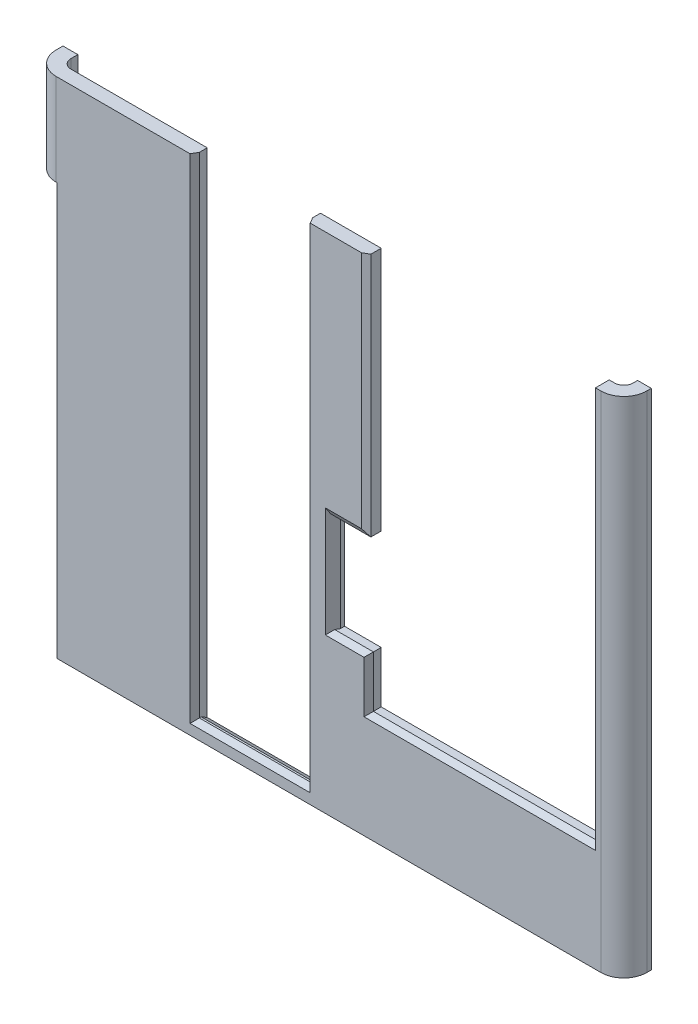
SolidWorks part; units mm, degrees
ref_plane "Front Plane" through (0, 0, 0) normal (0, 0, 1) x (1, 0, 0)
ref_plane "Top Plane" through (0, 0, 0) normal (0, 1, 0) x (1, 0, 0)
ref_plane "Right Plane" through (0, 0, 0) normal (1, 0, 0) x (0, 0, -1)
sketch "Sketch1" plane through (0, 0, 0) normal (0, 0, 1) x (1, 0, 0)
  line L0 (0, -3.575) -> (0, 3.575) construction
  line L1 (-60.5, 55) -> (60.5, 55)
  line L2 (-60.5, 55) -> (-60.5, -55)
  line L3 (-60.5, -55) -> (60.5, -55)
  line L4 (60.5, 55) -> (60.5, -55)
  line L5 (3.575, 0) -> (-3.575, 0) construction
  dimension "D1" = 60.5
  dimension "D2" = 60.5
  dimension "D3" = 55
  dimension "D4" = 55
extrude "Boss-Extrude1" add sketch "Sketch1" along normal blind 3
sketch "Sketch8" plane through (0, 0, 0) normal (0, 0, -1) x (-1, 0, 0)
  line L0 (60.5, -55) -> (-60.5, -55) construction
  line L1 (-60.5, 55) -> (-57.5, 55)
  line L2 (-60.5, 55) -> (-60.5, -55)
  line L3 (-60.5, -55) -> (-57.5, -55)
  line L4 (-57.5, 55) -> (-57.5, -55)
  dimension "D1" = 3
extrude "Boss-Extrude5" add sketch "Sketch8" along normal blind 3
fillet "Fillet4" radius 2 1 edges at (57.5, 0, 0)
fillet "Fillet5" radius 5 1 edges at (60.5, 0, 3)
sketch "Sketch9" plane through (0, 0, -3) normal (0, 0, -1) x (-1, 0, 0)
  line L0 (-57.5, 55) -> (-60.5, 55) construction
  line L1 (-59.5, 55) -> (-58.5, 55)
  line L2 (-59.5, 55) -> (-59.5, -55)
  line L3 (-59.5, -55) -> (-58.5, -55)
  line L4 (-58.5, 55) -> (-58.5, -55)
  line L5 (-60.5, -55) -> (-57.5, -55) construction
  line L6 (-60.5, 55) -> (-60.5, -55) construction
  line L7 (-57.5, -55) -> (-57.5, 55) construction
  dimension "D1" = 1
  dimension "D2" = 1
extrude "Boss-Extrude6" add sketch "Sketch9" along normal blind 2.5
sketch "Sketch10" plane through (0, 55, 0) normal (0, 1, 0) x (1, 0, 0)
  line L0 (58.5, 5.5) -> (58, 3)
  line L1 (57.5, 3) -> (58.5, 3) construction
  line L2 (58, 3) -> (58.5, 3)
  line L3 (58.5, 3) -> (58.5, 5.5)
extrude "Boss-Extrude7" add sketch "Sketch10" against normal through all
sketch "Sketch11" plane through (0, 0, 3) normal (0, 0, 1) x (1, 0, 0)
  line L0 (55.5, 55) -> (-60.5, 55) construction
  line L1 (-33.5, 55) -> (-8.75, 55)
  line L2 (-33.5, 55) -> (-33.5, -52)
  line L3 (-33.5, -52) -> (-8.75, -52)
  line L4 (-8.75, 55) -> (-8.75, -52)
  line L6 (-60.5, 55) -> (-60.5, -55) construction
  line L7 (57.5, -55) -> (57.5, 55) construction
  line L8 (4.5, 55) -> (54.3, 55)
  line L9 (4.5, 55) -> (4.5, -31.75)
  line L10 (4.5, -31.75) -> (54.3, -31.75)
  line L11 (54.3, 55) -> (54.3, -31.75)
  line L12 (-60.5, -55) -> (55.5, -55) construction
  dimension "D1" = 27
  dimension "D2" = 24.75
  dimension "D3" = 3.2
  dimension "D4" = 13.25
  dimension "D5" = 3
  dimension "D6" = 23.25
extrude "Cut-Extrude1" cut sketch "Sketch11" against normal up to surface (3 mm away) up to face at (-2.5, 0, 0)
chamfer "Chamfer1" distance 0.75 angle 60 3 edges at (-33.5, 1.5, 3) (-8.75, 1.5, 3) (-21.125, -52, 3)
chamfer "Chamfer2" distance 0.75 angle 60 1 edges at (-21.125, -52, 0)
sketch "Sketch13" plane through (0, 0, 3) normal (0, 0, 1) x (1, 0, 0)
  line L1 (4.5, 55) -> (4.5, -31.75) construction
  line L4 (-3.5, 1.5) -> (4.5, 1.5)
  line L5 (-3.5, 1.5) -> (-3.5, -20.5)
  line L7 (4.5, -20.5) -> (4.5, 1.5)
  line L9 (-3.5, -20.5) -> (-3.5, 1.5)
  line L10 (-3.5, -20.5) -> (4.5, -20.5)
  line L11 (4.5, 1.5) -> (4.5, -20.5)
  line M9 (4.5, -31.75) -> (4.5, 55)
  dimension "D1" = 8
extrude "Cut-Extrude4" cut sketch "Sketch13" against normal up to surface (3 mm away) contours L5 L10 L4 M9 up to face at (1.925, 4.25, 0)
chamfer "Chamfer3" distance 0.75 angle 60 5 edges at (4.5, 28.25, 3) (0.5, 1.5, 3) (29.4, -31.75, 3) (4.5, -26.125, 3) (0.5, -20.5, 3)
chamfer "Chamfer4" distance 1.2 angle 60 1 edges at (-3.5, -9.2255, 3)
sketch "Sketch14" plane through (-60.5, 0, 0) normal (-1, 0, 0) x (0, 0, 1)
  line L1 (0, 55) -> (3, 55)
  line L2 (0, 55) -> (0, -55)
  line L3 (0, -55) -> (3, -55)
  line L4 (3, 55) -> (3, -55)
extrude "Boss-Extrude8" add sketch "Sketch14" along normal blind 8
sketch "Sketch15" plane through (0, 0, 0) normal (0, 0, -1) x (-1, 0, 0)
  line L0 (33.5, 55) -> (68.5, 55) construction
  line L1 (68.5, -55) -> (65.25, -55)
  line L2 (68.5, -55) -> (68.5, 55)
  line L3 (68.5, 55) -> (65.25, 55)
  line L4 (65.25, -55) -> (65.25, 55)
  dimension "D1" = 3.25
extrude "Boss-Extrude9" add sketch "Sketch15" along normal blind 3.5
fillet "Fillet6" radius 2 1 edges at (-65.25, 0, 0)
fillet "Fillet7" radius 5 1 edges at (-68.5, 0, 3)
sketch "Sketch17" plane through (0, 0, -3.5) normal (0, 0, -1) x (-1, 0, 0)
  line L1 (68.5, -55) -> (63.25, -55)
  line L2 (68.5, -55) -> (68.5, 35)
  line L3 (68.5, 35) -> (63.25, 35)
  line L4 (63.25, -55) -> (63.25, 35)
  dimension "D1" = 5.25
  dimension "D2" = 90
extrude "Cut-Extrude5" cut sketch "Sketch17" against normal up to surface (6.5 mm away)
sketch "Sketch18" plane through (0, 55, 0) normal (0, 1, 0) x (1, 0, 0)
  line L1 (57.5, 3) -> (60.5, 3)
  line L2 (57.5, 3) -> (57.5, 8.1011)
  line L3 (57.5, 8.1011) -> (60.5, 8.1011)
  line L4 (60.5, 3) -> (60.5, 8.1011)
extrude "Cut-Extrude6" cut sketch "Sketch18" against normal up to surface (110 mm away) up to face at (38.1208, -55, -1.6292)
